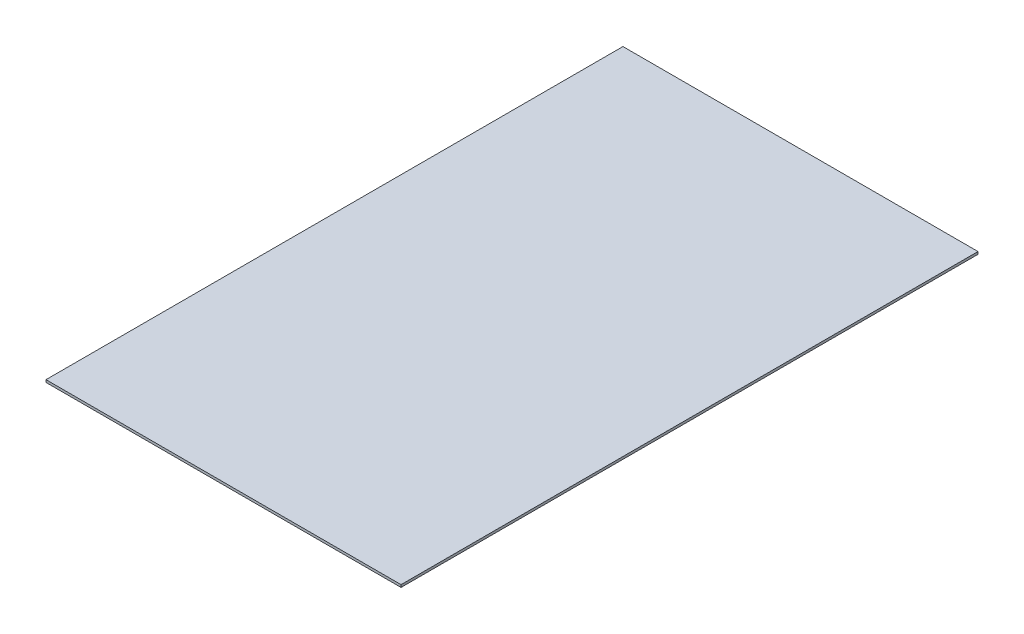
SolidWorks part; units mm, degrees
ref_plane "Front Plane" through (0, 0, 0) normal (0, 0, 1) x (1, 0, 0)
ref_plane "Top Plane" through (0, 0, 0) normal (0, 1, 0) x (1, 0, 0)
ref_plane "Right Plane" through (0, 0, 0) normal (1, 0, 0) x (0, 0, -1)
sketch "Sketch1" plane through (0, 0, 0) normal (0, 1, 0) x (1, 0, 0)
  line L1 (0, 0) -> (101.6, 0)
  line L2 (0, 0) -> (0, -165.1)
  line L3 (0, -165.1) -> (101.6, -165.1)
  line L4 (101.6, 0) -> (101.6, -165.1)
  dimension "D1" = 165.1
  dimension "D2" = 101.6
extrude "Boss-Extrude1" add sketch "Sketch1" along normal blind 0.7
